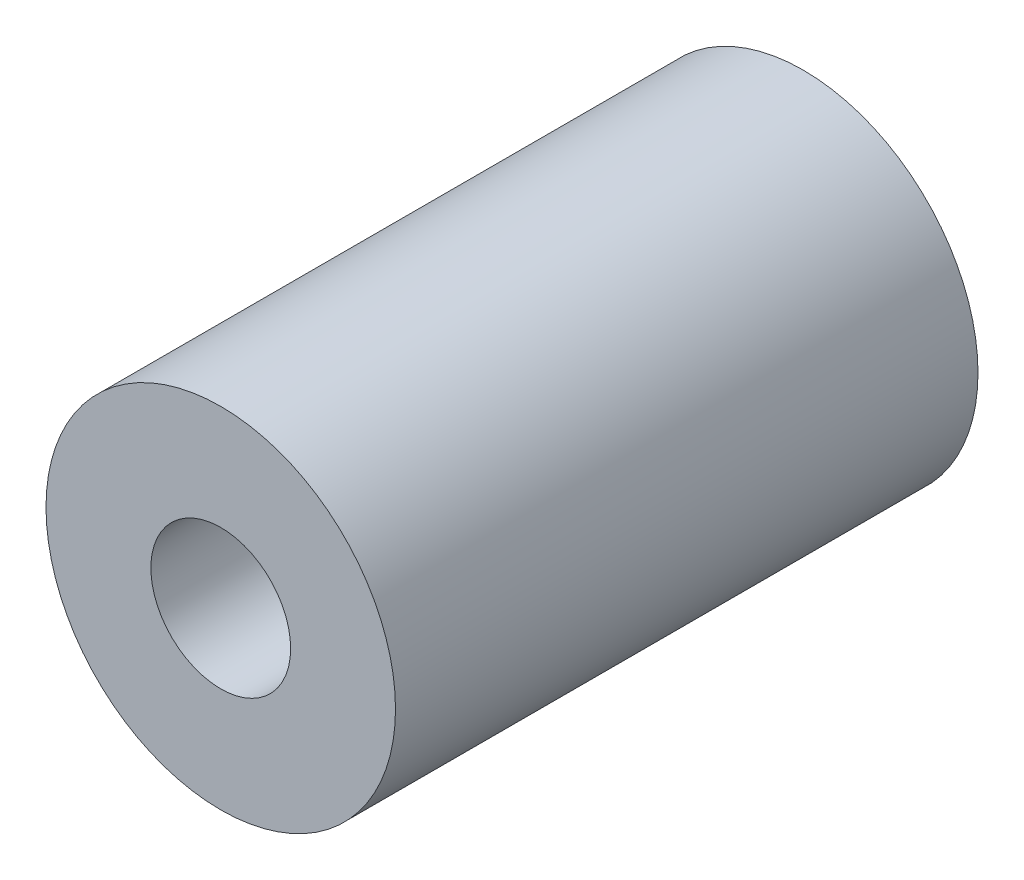
SolidWorks part; units mm, degrees
ref_plane "前视基准面" through (0, 0, 0) normal (0, 0, 1) x (1, 0, 0)
ref_plane "上视基准面" through (0, 0, 0) normal (0, 1, 0) x (1, 0, 0)
ref_plane "右视基准面" through (0, 0, 0) normal (1, 0, 0) x (0, 0, -1)
other "Configuration Table"
sketch "草图1" plane through (0, 0, 0) normal (0, 0, 1) x (1, 0, 0)
  circle A0 centre (0, 0) radius 6
  circle A1 centre (0, 0) radius 15
  dimension "D1" = 12
  dimension "D2" = 30
extrude "凸台-拉伸1" add sketch "草图1" along normal blind 50
